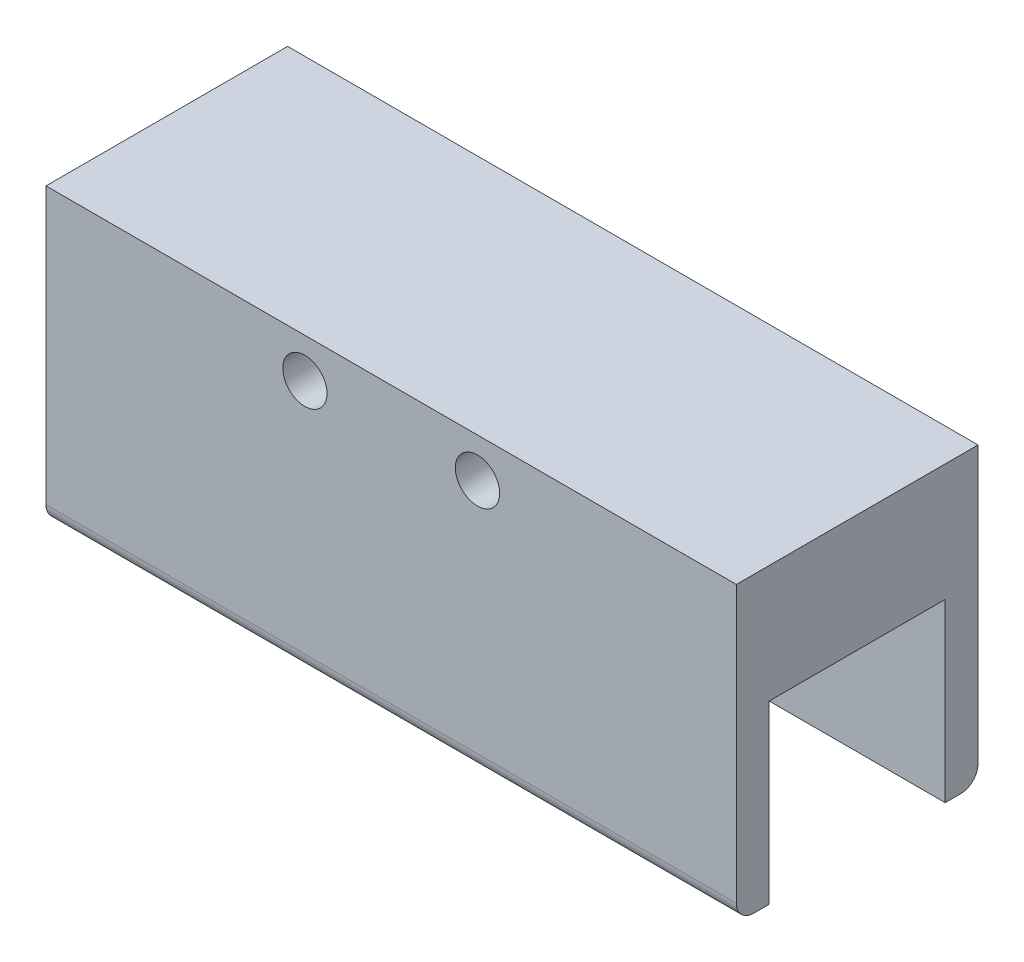
SolidWorks part; units mm, degrees
ref_plane "Front Plane" through (0, 0, 0) normal (0, 0, 1) x (1, 0, 0)
ref_plane "Top Plane" through (0, 0, 0) normal (0, 1, 0) x (1, 0, 0)
ref_plane "Right Plane" through (0, 0, 0) normal (1, 0, 0) x (0, 0, -1)
sketch "Sketch2" plane through (0, 0, 0) normal (0, 0, 1) x (1, 0, 0)
  line L1 (0, 0) -> (200, 0)
  line L2 (0, 0) -> (0, 85)
  line L3 (0, 85) -> (200, 85)
  line L4 (200, 0) -> (200, 85)
  dimension "D1" = 200
  dimension "D2" = 85
extrude "Boss-Extrude1" add sketch "Sketch2" along normal blind 70
sketch "Sketch3" plane through (200, 0, 0) normal (1, 0, 0) x (0, 0, -1)
  line L0 (-70, 0) -> (0, 0) construction
  line L1 (-60.5, -86.8794) -> (-9.5, -86.8794)
  line L2 (-60.5, 0) -> (-60.5, 51)
  line L3 (-60.5, 51) -> (-9.5, 51)
  line L4 (-9.5, 0) -> (-9.5, 51)
  line L5 (-35, 0) -> (-9.5, 51) construction
  line L6 (-60.5, 51) -> (-35, 0) construction
  line L7 (-60.5, 0) -> (-9.5, 0)
  point P0 (-35, 0)
  line M8 (-70, 0) -> (0, 0)
  dimension "D1" = 51
  dimension "D2" = 51
  dimension "D3" = 0
extrude "Cut-Extrude1" cut sketch "Sketch3" against normal through all contours L4 L3 L2 M8
fillet "Fillet1" radius 5 2 edges at (100, 0, 0) (100, 0, 70)
sketch "Sketch4" plane through (0, 0, 70) normal (0, 0, 1) x (1, 0, 0)
  line L0 (200, 5) -> (200, 85) construction
  line L1 (200, 85) -> (0, 85) construction
  line L2 (100, 85) -> (100, 5) construction
  line L3 (0, 5) -> (200, 5) construction
  circle A0 centre (125, 73.585) radius 6.415
  circle A1 centre (75, 73.585) radius 6.415
  dimension "D1" = 75
  dimension "D2" = 12.83
  dimension "D3" = 11.415
extrude "Cut-Extrude2" cut sketch "Sketch4" against normal through all
